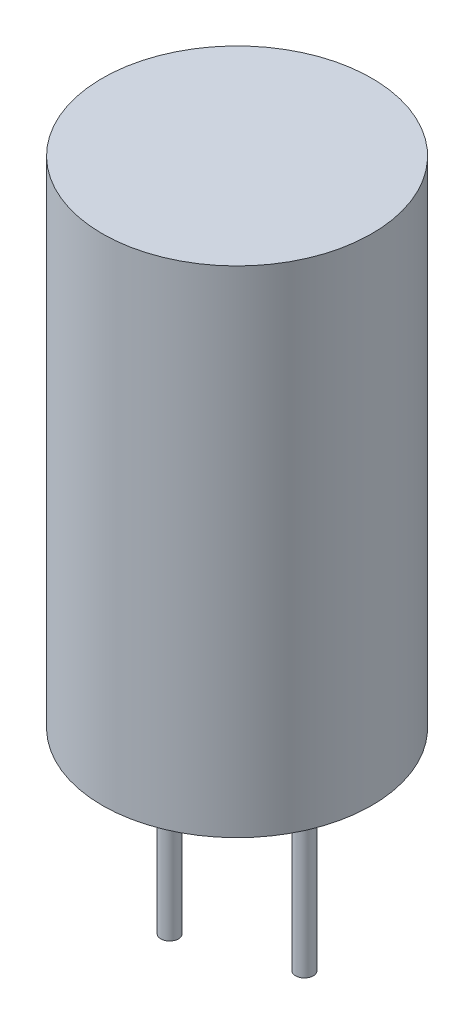
SolidWorks part; units mm, degrees
ref_plane "前视基准面" through (0, 0, 0) normal (0, 0, 1) x (1, 0, 0)
ref_plane "上视基准面" through (0, 0, 0) normal (0, 1, 0) x (1, 0, 0)
ref_plane "右视基准面" through (0, 0, 0) normal (1, 0, 0) x (0, 0, -1)
sketch "草图1" plane through (0, 0, 0) normal (0, 1, 0) x (1, 0, 0)
  circle A0 centre (0, 0) radius 7.62
  dimension "D1" = 15.24
extrude "拉伸1" add sketch "草图1" along normal blind 28
sketch "草图2" plane through (0, 0, 0) normal (0, -1, 0) x (1, 0, 0)
  line L0 (4.8023, 0) -> (-11.2367, 0) construction
  circle A0 centre (-3.81, 0) radius 0.5
  dimension "D2" = 1
  dimension "D1" = 3.81
extrude "拉伸2" add sketch "草图2" along normal blind 12
sketch "草图3" plane through (0, 0, 0) normal (0, -1, 0) x (1, 0, 0)
  line L0 (7.1249, 0) -> (-2.8562, 0) construction
  circle A0 centre (3.81, 0) radius 0.5
  dimension "D1" = 1
  dimension "D2" = 3.81
extrude "拉伸3" add sketch "草图3" along normal blind 10
